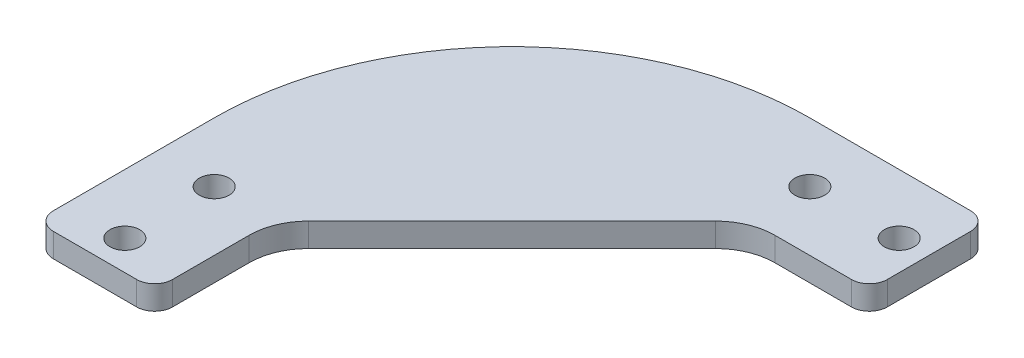
SolidWorks part; units mm, degrees
material "PA Type 6"
ref_plane "Front Plane" through (0, 0, 0) normal (0, 0, 1) x (1, 0, 0)
ref_plane "Top Plane" through (0, 0, 0) normal (0, 1, 0) x (1, 0, 0)
ref_plane "Right Plane" through (0, 0, 0) normal (1, 0, 0) x (0, 0, -1)
sketch "Sketch1" plane through (0, 0, 0) normal (0, 1, 0) x (1, 0, 0)
  line L2 (0, 30.7616) -> (0, -31.9345) construction
  line L3 (-37.514, 0) -> (35.3317, 0) construction
  line L4 (-50, 0) -> (-50, -27)
  line L5 (-47, -30) -> (-33, -30)
  line L6 (-30, -27) -> (-30, -14.1421)
  line L7 (0, 50) -> (27, 50)
  line L8 (30, 47) -> (30, 33)
  line L9 (27, 30) -> (14.1421, 30)
  line L10 (7.0711, 27.0711) -> (-27.0711, -7.0711)
  line L11 (-40, -30) -> (-40, 24.2665) construction
  line L12 (30, 40) -> (-23.5548, 40) construction
  arc A1 (0, 50) -> (-50, 0) centre (0, 0) ccw
  arc A2 (-27.0711, -7.0711) -> (-30, -14.1421) centre (-20, -14.1421) ccw
  arc A3 (7.0711, 27.0711) -> (14.1421, 30) centre (14.1421, 20) cw
  arc A4 (27, 50) -> (30, 47) centre (27, 47) cw
  arc A5 (30, 33) -> (27, 30) centre (27, 33) cw
  arc A6 (-33, -30) -> (-30, -27) centre (-33, -27) ccw
  arc A7 (-50, -27) -> (-47, -30) centre (-47, -27) ccw
  circle A8 centre (-40, -10) radius 2.5
  circle A9 centre (-40, -25) radius 2.5
  circle A10 centre (10, 40) radius 2.5
  circle A11 centre (25, 40) radius 2.5
  point P16 (-30, -10)
  point P19 (10, 30)
  point P22 (30, 50)
  point P25 (30, 30)
  point P28 (-30, -30)
  point P31 (-50, -30)
  dimension "D1" = 100
  dimension "D2" = 20
  dimension "D8" = 10
  dimension "D9" = 3
  dimension "D10" = 5
  dimension "D11" = 5
  dimension "D14" = 5
  dimension "D15" = 5
  dimension "D3" = 30
  dimension "D4" = 20
  dimension "D5" = 30
  dimension "D6" = 20
  dimension "D7" = 20
  dimension "D12" = 10
  dimension "D13" = 25
  dimension "D16" = 10
  dimension "D17" = 25
extrude "Boss-Extrude1" add sketch "Sketch1" along normal blind 4
